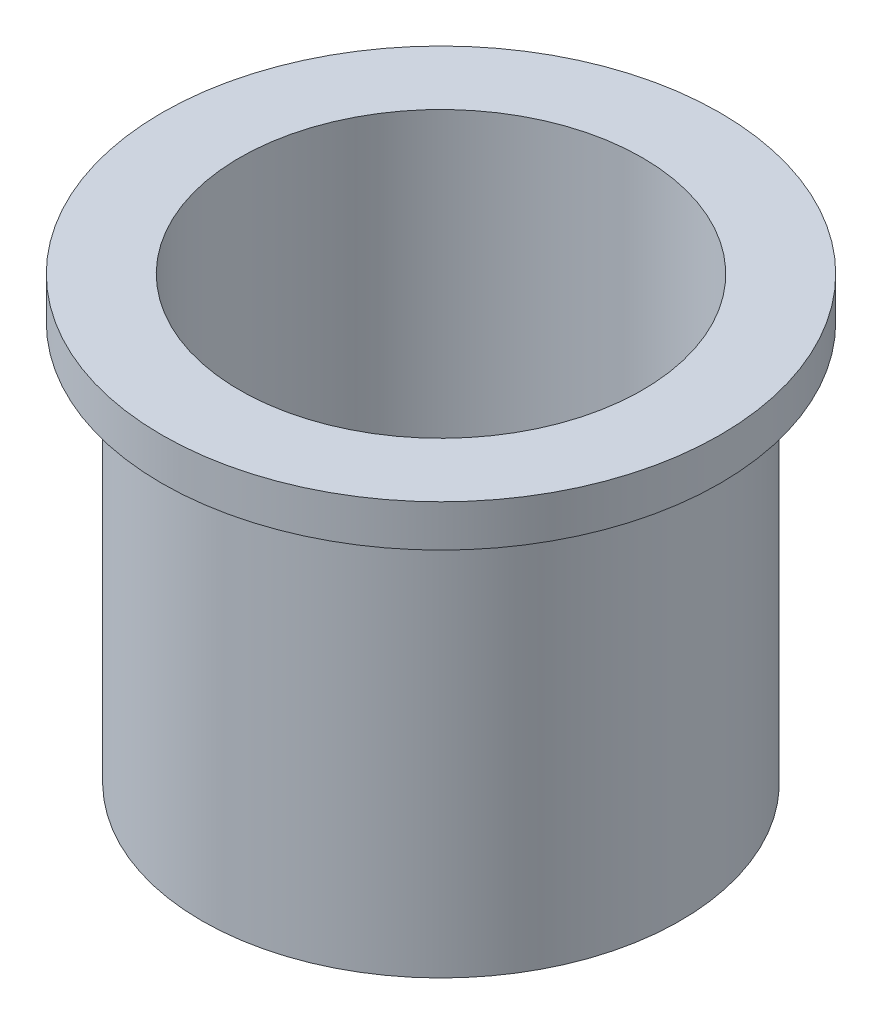
SolidWorks part; units mm, degrees
other "Acetal Torque Guide Bush Locating"
ref_plane "Front Plane" through (0, 0, 0) normal (0, 0, 1) x (1, 0, 0)
ref_plane "Top Plane" through (0, 0, 0) normal (0, 1, 0) x (1, 0, 0)
ref_plane "Right Plane" through (0, 0, 0) normal (1, 0, 0) x (0, 0, -1)
sketch3d "Guide bush barrel sketch datum points"
  point P0 (-20.2917, -105.98, 0)
  point P1 (-10.2917, -105.98, 0)
  point P2 (-20.2917, -105.98, -10)
ref_plane "Guide bush barrel sketch plane" through (0, -105.98, 0) normal (0, 1, 0) x (1, 0, 0)
sketch "Guide bush barrel sketch" plane through (0, -105.98, 0) normal (0, 1, 0) x (1, 0, 0)
  circle A0 centre (-20.2917, 0) radius 6
extrude "Guide bush barrel" add sketch "Guide bush barrel sketch" along normal blind 10 separate body
sketch3d "Guide bush flange sketch datum points"
  point P0 (-20.2917, -95.98, 0)
  point P1 (-10.2917, -95.98, 0)
  point P2 (-20.2917, -95.98, -10)
ref_plane "Guide bush flange sketch plane" through (0, -95.98, 0) normal (0, 1, 0) x (1, 0, 0)
sketch "Guide bush flange sketch" plane through (0, -95.98, 0) normal (0, 1, 0) x (1, 0, 0)
  circle A0 centre (-20.2917, 0) radius 7
extrude "Guide bush flange" add sketch "Guide bush flange sketch" along normal blind 1.05
sketch3d "Running bore sketch datum points"
  point P0 (-20.2917, -106.08, 0)
  point P1 (-10.2917, -106.08, 0)
  point P2 (-20.2917, -106.08, -10)
ref_plane "Running bore sketch plane" through (0, -106.08, 0) normal (0, 1, 0) x (1, 0, 0)
sketch "Running bore sketch" plane through (0, -106.08, 0) normal (0, 1, 0) x (1, 0, 0)
  circle A0 centre (-20.2917, 0) radius 5.05
extrude "Running bore" cut sketch "Running bore sketch" along normal blind 11.25
